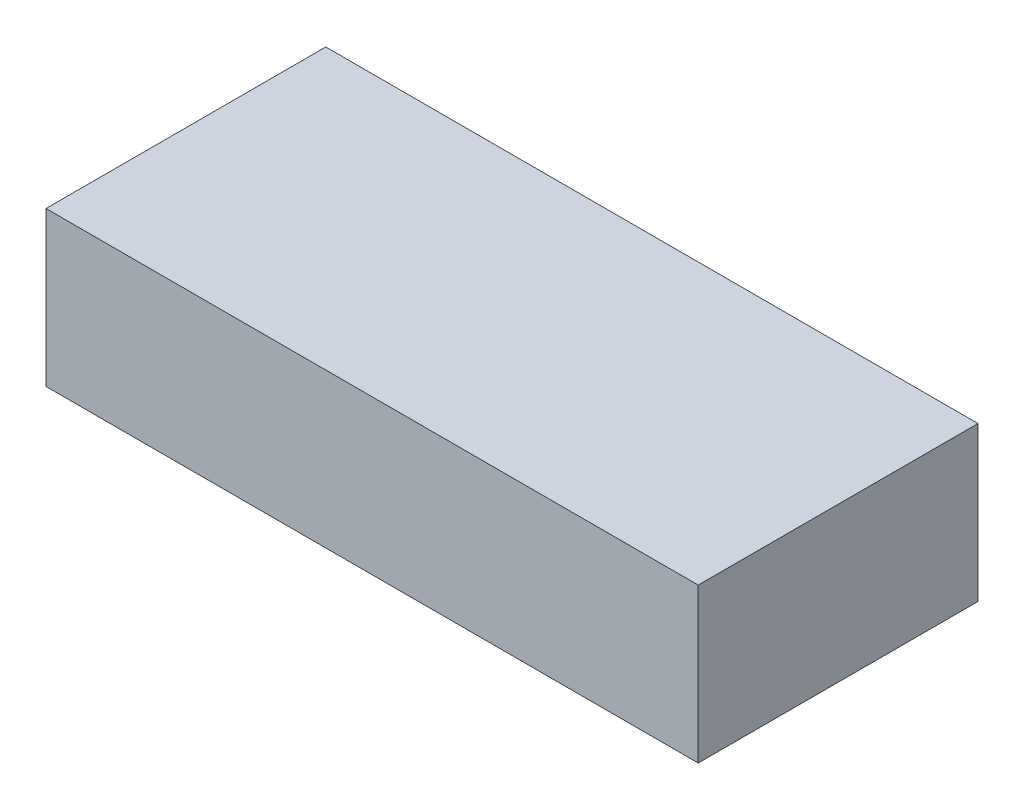
SolidWorks part; units mm, degrees
ref_plane "Plan de face" through (0, 0, 0) normal (0, 0, 1) x (1, 0, 0)
ref_plane "Plan de dessus" through (0, 0, 0) normal (0, 1, 0) x (1, 0, 0)
ref_plane "Plan de droite" through (0, 0, 0) normal (1, 0, 0) x (0, 0, -1)
sketch "Esquisse1" plane through (0, 0, 0) normal (0, 1, 0) x (1, 0, 0)
  line L0 (0, 0) -> (74.69, 0)
  line L1 (74.69, 0) -> (74.69, 32.04)
  line L2 (74.69, 32.04) -> (0, 32.04)
  line L3 (0, 32.04) -> (0, 0)
extrude "Boss.-Extru.1" add sketch "Esquisse1" along normal blind 17.65 contours L2 L3 L0 L1
